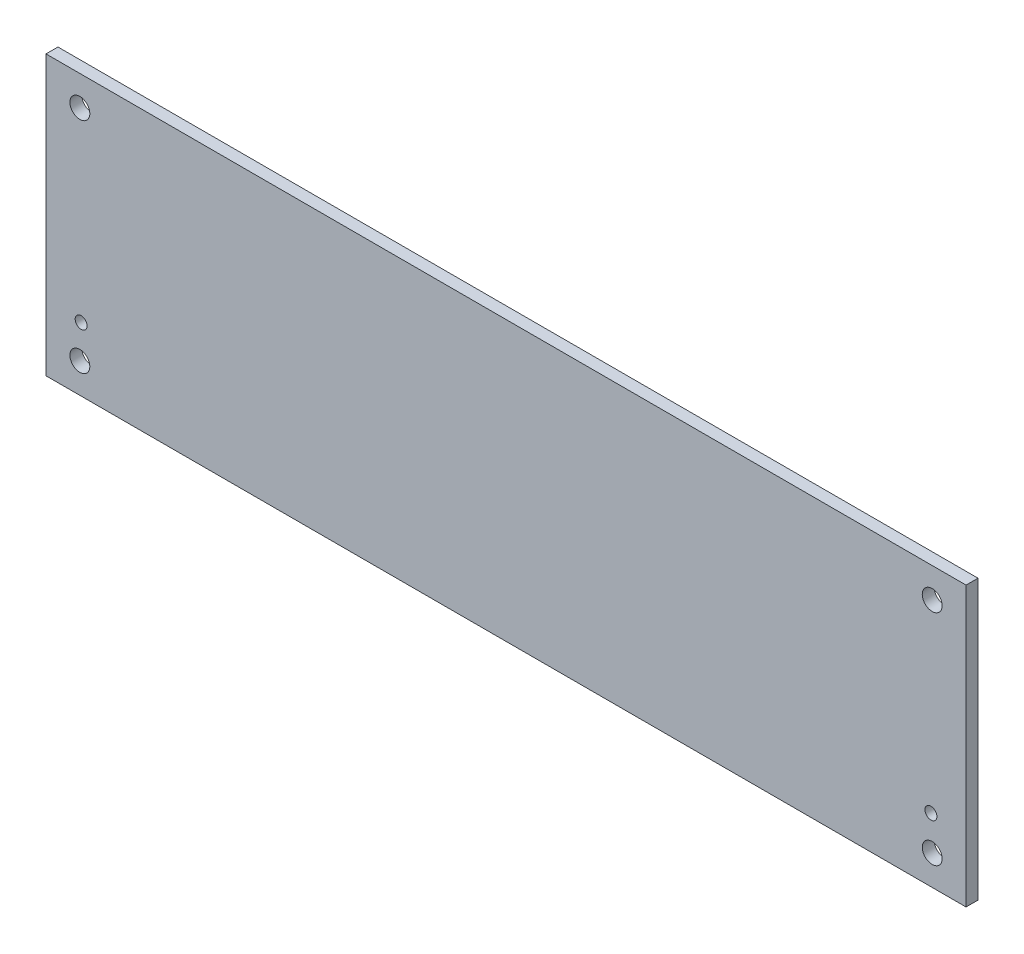
SolidWorks part; units mm, degrees
ref_plane "前视基准面" through (0, 0, 0) normal (0, 0, 1) x (1, 0, 0)
ref_plane "上视基准面" through (0, 0, 0) normal (0, 1, 0) x (1, 0, 0)
ref_plane "右视基准面" through (0, 0, 0) normal (1, 0, 0) x (0, 0, -1)
sketch "草图1" plane through (0, 0, 0) normal (0, 0, 1) x (1, 0, 0)
  line L1 (115.5, 35) -> (-115.5, 35)
  line L2 (115.5, 35) -> (115.5, -35)
  line L3 (115.5, -35) -> (-115.5, -35)
  line L4 (-115.5, 35) -> (-115.5, -35)
  line L5 (0, -35) -> (0, 35) construction
  line L6 (115.5, 0) -> (-115.5, 0) construction
  circle A0 centre (-107, 27.5) radius 2.5
  circle A1 centre (-107, -27.5) radius 2.5
  circle A2 centre (107, -27.5) radius 2.5
  circle A3 centre (107, 27.5) radius 2.5
  point P0 (0, 0)
  dimension "D4" = 5
  dimension "D1" = 231
  dimension "D2" = 70
  dimension "D3" = 27.5
  dimension "D5" = 107
extrude "凸台-拉伸1" add sketch "草图1" along normal blind 3
sketch "草图4" plane through (0, 0, 3) normal (0, 0, 1) x (1, 0, 0)
  circle A2 centre (-106.6775, -19) radius 1.5
  circle A3 centre (-107, -27.5) radius 2.5 construction
  dimension "D1" = 8.5
extrude "切除-拉伸1" cut sketch "草图4" against normal blind 10
mirror "镜向1" about plane through (0, 0, 0) normal (1, 0, 0) of "切除-拉伸1"
